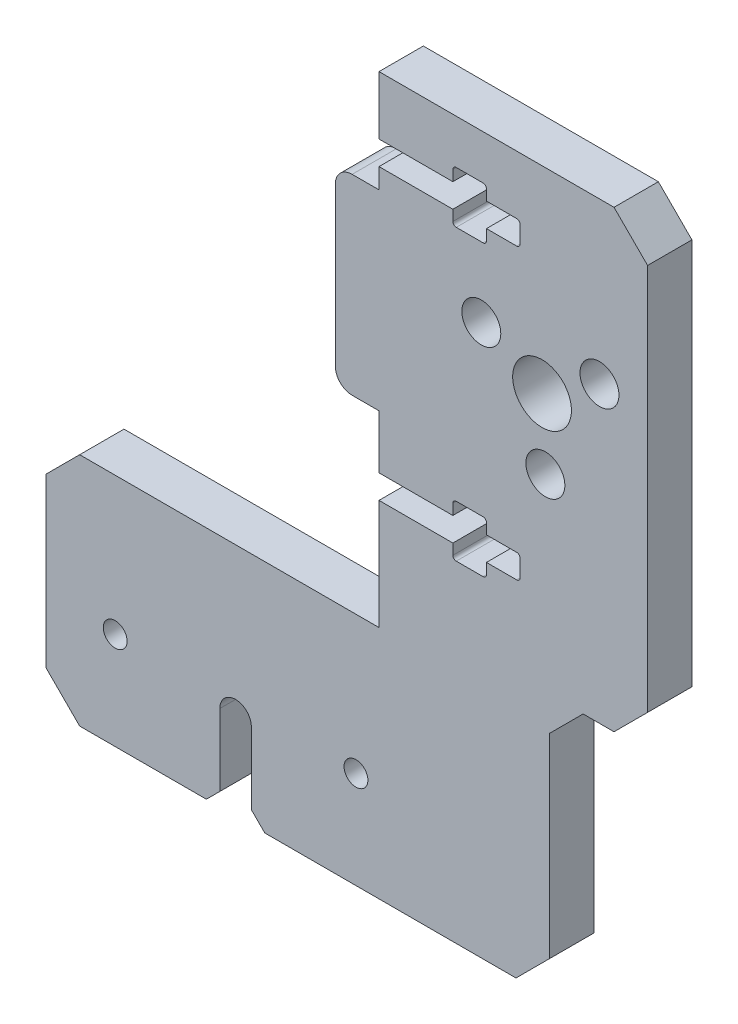
SolidWorks part; units mm, degrees
ref_plane "Front Plane" through (0, 0, 0) normal (0, 0, 1) x (1, 0, 0)
ref_plane "Top Plane" through (0, 0, 0) normal (0, 1, 0) x (1, 0, 0)
ref_plane "Right Plane" through (0, 0, 0) normal (1, 0, 0) x (0, 0, -1)
sketch "Model" plane through (0, 0, 0) normal (0, 0, 1) x (1, 0, 0)
  line L0 (-24.79, -12.5) -> (-19.79, -17.5)
  line L1 (-19.79, 17.5) -> (-24.79, 12.5)
  line L2 (35.79, 33.9) -> (35.79, 32.315)
  line L3 (36.29, 31.815) -> (40.29, 31.815)
  line L4 (40.79, 32.315) -> (40.79, 33.9)
  line L5 (40.79, 33.9) -> (45.29, 33.9)
  line L6 (45.79, 34.4) -> (45.79, 36.95)
  line L7 (45.29, 37.45) -> (40.79, 37.45)
  line L8 (40.79, 37.45) -> (40.79, 39.035)
  line L9 (40.29, 39.535) -> (36.29, 39.535)
  line L10 (35.79, 39.035) -> (35.79, 37.45)
  line L11 (20.79, 45.45) -> (24.79, 45.45)
  line L12 (18.29, 71.45) -> (18.29, 47.95)
  line L13 (24.79, 73.95) -> (20.79, 73.95)
  line L14 (35.79, 76.95) -> (35.79, 75.365)
  line L15 (36.29, 74.865) -> (40.29, 74.865)
  line L16 (40.79, 75.365) -> (40.79, 76.95)
  line L17 (40.79, 76.95) -> (45.29, 76.95)
  line L18 (45.79, 77.45) -> (45.79, 80)
  line L19 (45.29, 80.5) -> (40.79, 80.5)
  line L20 (40.79, 80.5) -> (40.79, 82.085)
  line L21 (40.29, 82.585) -> (36.29, 82.585)
  line L22 (35.79, 82.085) -> (35.79, 80.5)
  line L23 (64.79, 84.1999) -> (59.79, 89.1999)
  line L24 (59.79, 21.555) -> (64.79, 26.555)
  line L25 (50.19, 16.555) -> (55.19, 21.555)
  line L26 (45.19, -17.5) -> (50.19, -12.5)
  line L27 (5.7795, -15.5) -> (7.7795, -17.5)
  line L28 (5.7795, -15.5) -> (5.7795, -4.8)
  line L29 (1.0805, -4.8) -> (1.0805, -15.5)
  line L30 (-0.9195, -17.5) -> (1.0805, -15.5)
  line L31 (24.79, 17.5) -> (-19.79, 17.5)
  line L32 (24.79, 76.95) -> (24.79, 73.95)
  line L33 (59.79, 89.1999) -> (24.79, 89.1999)
  line L34 (64.79, 26.555) -> (64.79, 84.1999)
  line L35 (55.19, 21.555) -> (59.79, 21.555)
  line L36 (50.19, -12.5) -> (50.19, 16.555)
  line L37 (7.7795, -17.5) -> (45.19, -17.5)
  line L38 (-24.79, 12.5) -> (-24.79, -12.5)
  line L39 (24.79, 33.9) -> (24.79, 17.5)
  line L40 (24.79, 45.45) -> (24.79, 37.45)
  line L41 (24.79, 89.1999) -> (24.79, 80.5)
  line L42 (24.79, 33.9) -> (35.79, 33.9)
  line L43 (35.79, 37.45) -> (24.79, 37.45)
  line L44 (24.79, 76.95) -> (35.79, 76.95)
  line L45 (35.79, 80.5) -> (24.79, 80.5)
  line L46 (-19.79, -17.5) -> (-0.9195, -17.5)
  circle A0 centre (49.072, 59.8129) radius 4.375
  circle A1 centre (57.6212, 65.3212) radius 2.9
  circle A2 centre (40.0272, 64.4626) radius 2.9
  circle A3 centre (49.5677, 49.655) radius 2.9
  circle A4 centre (-14.5, -3.025) radius 1.775
  circle A5 centre (21.36, -3.025) radius 1.775
  arc A6 (35.79, 32.315) -> (36.29, 31.815) centre (36.29, 32.315) ccw
  arc A7 (40.29, 31.815) -> (40.79, 32.315) centre (40.29, 32.315) ccw
  arc A8 (45.29, 33.9) -> (45.79, 34.4) centre (45.29, 34.4) ccw
  arc A9 (45.79, 36.95) -> (45.29, 37.45) centre (45.29, 36.95) ccw
  arc A10 (40.79, 39.035) -> (40.29, 39.535) centre (40.29, 39.035) ccw
  arc A11 (36.29, 39.535) -> (35.79, 39.035) centre (36.29, 39.035) ccw
  arc A12 (18.29, 47.95) -> (20.79, 45.45) centre (20.79, 47.95) ccw
  arc A13 (20.79, 73.95) -> (18.29, 71.45) centre (20.79, 71.45) ccw
  arc A14 (35.79, 75.365) -> (36.29, 74.865) centre (36.29, 75.365) ccw
  arc A15 (40.29, 74.865) -> (40.79, 75.365) centre (40.29, 75.365) ccw
  arc A16 (45.29, 76.95) -> (45.79, 77.45) centre (45.29, 77.45) ccw
  arc A17 (45.79, 80) -> (45.29, 80.5) centre (45.29, 80) ccw
  arc A18 (40.79, 82.085) -> (40.29, 82.585) centre (40.29, 82.085) ccw
  arc A19 (36.29, 82.585) -> (35.79, 82.085) centre (36.29, 82.085) ccw
  arc A20 (5.7795, -4.8) -> (1.0805, -4.8) centre (3.43, -4.8) ccw
extrude "Boss-Extrude1" add sketch "Model" along normal blind 6.6
